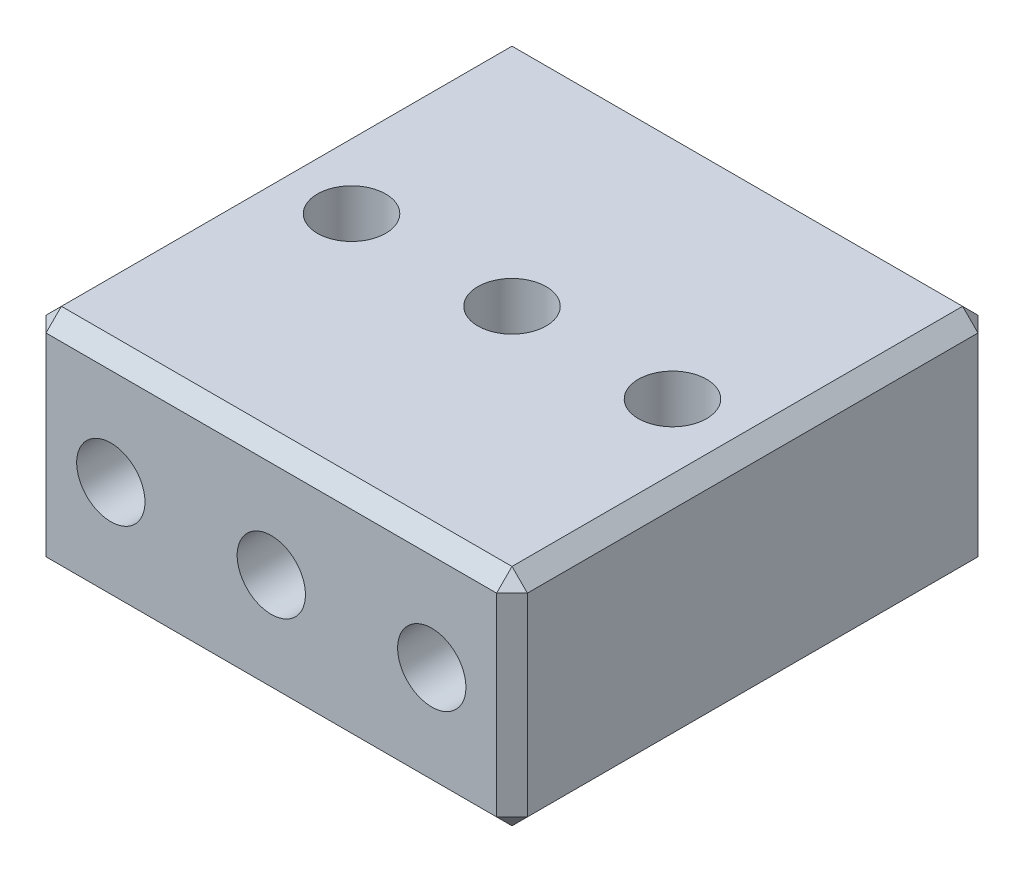
SolidWorks part; units mm, degrees
material "PET"
ref_plane "Front" through (0, 0, 0) normal (0, 0, 1) x (1, 0, 0)
ref_plane "Top" through (0, 0, 0) normal (0, 1, 0) x (1, 0, 0)
ref_plane "Right" through (0, 0, 0) normal (1, 0, 0) x (0, 0, -1)
sketch "Sketch1" plane through (0, 0, 0) normal (1, 0, 0) x (0, 0, -1)
  line L1 (23.8125, -11.1125) -> (-23.8125, -11.1125)
  line L2 (23.8125, -11.1125) -> (23.8125, 11.1125)
  line L3 (23.8125, 11.1125) -> (-23.8125, 11.1125)
  line L4 (-23.8125, -11.1125) -> (-23.8125, 11.1125)
  line L5 (23.8125, -11.1125) -> (-23.8125, 11.1125) construction
  line L6 (23.8125, 11.1125) -> (-23.8125, -11.1125) construction
  point P0 (0, 0)
  dimension "D1" = 22.225
  dimension "D2" = 47.625
extrude "Boss-Extrude1" add sketch "Sketch1" along normal mid plane 47.625
hole_wizard "1/4 Clearance Hole1" positions "Sketch2" profile "Sketch3" hole size "1/4" standard "ANSI Inch" end condition through all
sketch "Sketch2" plane through (0, 0, 23.8125) normal (0, 0, 1) x (1, 0, 0)
  line L0 (-15.875, 0) -> (15.875, 0) construction
  point P0 (0, 0)
  point P3 (-15.875, 0)
  point P5 (15.875, 0)
  point P12 (0, 0)
  dimension "D1" = 15.875
sketch "Sketch3" plane through (0, 0, 23.8125) normal (1, 0, 0) x (0, -1, 0)
  line L0 (0, 0) -> (0, 47.625)
  line L1 (0, 47.625) -> (3.3782, 47.625)
  line L2 (3.3782, 47.625) -> (3.3782, 0)
  line L5 (3.3782, 0) -> (0, 0)
  line L11 (0, -6.35) -> (0, 107.95) construction
  dimension "Thru Hole Dia." = 6.7564
  dimension "Thru Hole Depth" = 47.625
hole_wizard "1/4 Clearance Hole2" positions "Sketch4" profile "Sketch5" hole size "1/4" standard "ANSI Inch" end condition through all
sketch "Sketch4" plane through (0, 11.1125, 0) normal (0, 1, 0) x (1, 0, 0)
  line L0 (-15.875, 0) -> (15.875, 0) construction
  point P1 (-15.875, 0)
  point P2 (15.875, 0)
  point P8 (0, 0)
  dimension "D1" = 15.875
sketch "Sketch5" plane through (-15.875, 11.1125, 0) normal (1, 0, 0) x (0, 0, 1)
  line L0 (0, 0) -> (0, 22.225)
  line L1 (0, 22.225) -> (3.3782, 22.225)
  line L2 (3.3782, 22.225) -> (3.3782, 0)
  line L5 (3.3782, 0) -> (0, 0)
  line L11 (0, -6.35) -> (0, 107.95) construction
  dimension "Thru Hole Dia." = 6.7564
  dimension "Thru Hole Depth" = 22.225
chamfer "Chamfer1" distance 1.524 angle 45 12 edges at (-23.8125, -11.1125, 0) (0, -11.1125, -23.8125) (-23.8125, 0, -23.8125) (0, 11.1125, -23.8125) (-23.8125, 11.1125, 0) (-23.8125, 0, 23.8125) (0, -11.1125, 23.8125) (23.8125, 0, -23.8125) (23.8125, -11.1125, 0) (23.8125, 11.1125, 0) (23.8125, 0, 23.8125) (0, 11.1125, 23.8125)
